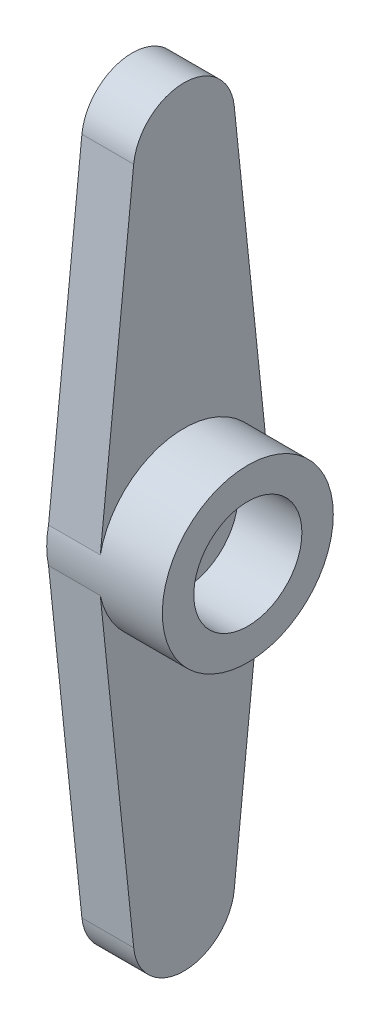
SolidWorks part; units mm, degrees
material "Custom Plastic"
ref_plane "Front Plane" through (0, 0, 0) normal (0, 0, 1) x (1, 0, 0)
ref_plane "Top Plane" through (0, 0, 0) normal (0, 1, 0) x (1, 0, 0)
ref_plane "Right Plane" through (0, 0, 0) normal (1, 0, 0) x (0, 0, -1)
sketch "Sketch1" plane through (0, 0, 0) normal (1, 0, 0) x (0, 0, -1)
  circle A0 centre (0, 0) radius 4.318
  dimension "D1" = 8.636
extrude "Boss-Extrude1" add sketch "Sketch1" along normal blind 5.842
sketch "Sketch2" plane through (0, 0, 0) normal (-1, 0, 0) x (0, 0, 1)
  line L0 (-4.318, 0) -> (-2.54, 17.1408)
  line L1 (4.318, 0) -> (2.54, 17.1408)
  line L2 (0, 0) -> (0, 16.8813) construction
  line L3 (-4.6778, 19.431) -> (3.553, 19.431) construction
  line L4 (0, 0) -> (6.9943, 0) construction
  circle A0 centre (0, 0) radius 4.318 construction
  arc A1 (-2.54, 17.1408) -> (2.54, 17.1408) centre (0, 16.8774) cw
  circle A2 centre (0, 0) radius 4.318
  circle M6 centre (0, 0) radius 4.318
  dimension "D1" = 19.431
  dimension "D2" = 5.08
extrude "Boss-Extrude2" add sketch "Sketch2" against normal blind 2.6162 contours A1 L0 L1 M6
mirror "Mirror1" about plane through (0, 0, 0) normal (0, 1, 0) of "Boss-Extrude2"
sketch "Sketch3" plane through (5.842, 0, 0) normal (1, 0, 0) x (0, 0, -1)
  circle A0 centre (0, 0) radius 2.7305
  circle A1 centre (0, 0) radius 4.318 construction
  dimension "D1" = 1.5875
extrude "Cut-Extrude1" cut sketch "Sketch3" against normal blind 3.2258
